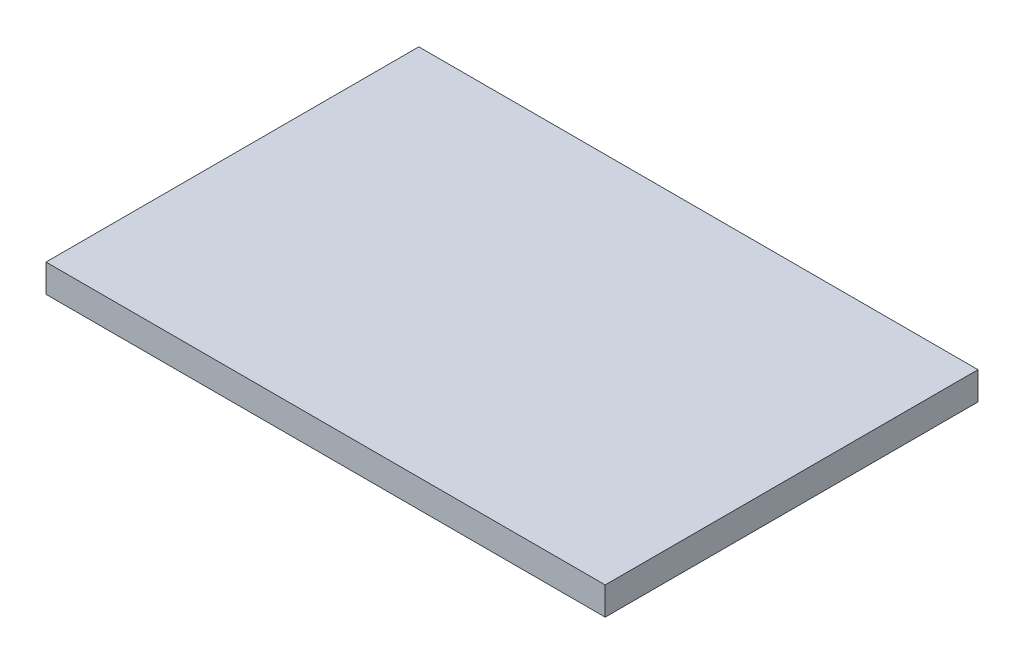
SolidWorks part; units mm, degrees
ref_plane "前视" through (0, 0, 0) normal (0, 0, 1) x (1, 0, 0)
ref_plane "上视" through (0, 0, 0) normal (0, 1, 0) x (1, 0, 0)
ref_plane "右视" through (0, 0, 0) normal (1, 0, 0) x (0, 0, -1)
sketch "Sketch1" plane through (0, 0, 0) normal (0, 1, 0) x (1, 0, 0)
  line L1 (0, 0) -> (60, 0)
  line L2 (0, 0) -> (0, 40)
  line L3 (0, 40) -> (60, 40)
  line L4 (60, 0) -> (60, 40)
  dimension "D1" = 60
  dimension "D2" = 40
extrude "Extrude1" add sketch "Sketch1" along normal blind 3
